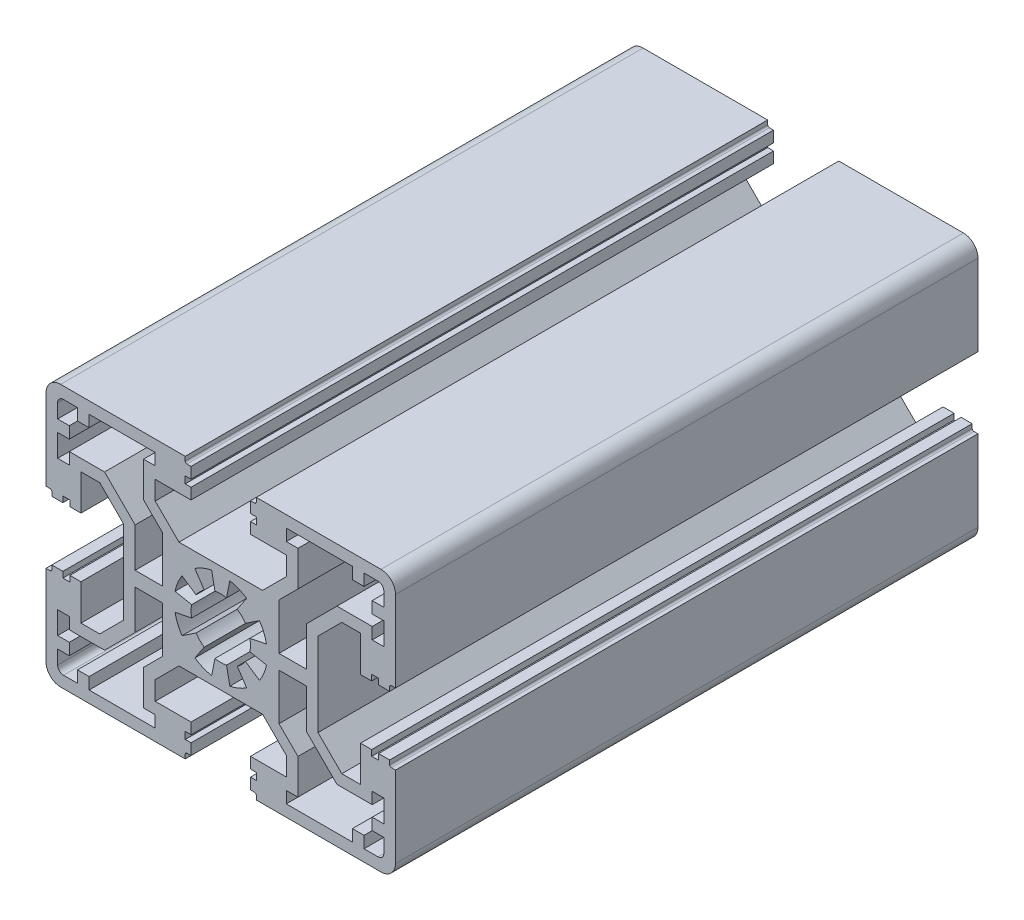
SolidWorks part; units mm, degrees
ref_plane "前视基准面" through (0, 0, 0) normal (0, 0, 1) x (1, 0, 0)
ref_plane "上视基准面" through (0, 0, 0) normal (0, 1, 0) x (1, 0, 0)
ref_plane "右视基准面" through (0, 0, 0) normal (1, 0, 0) x (0, 0, -1)
sketch "草图1" plane through (0, 0, 0) normal (0, 0, 1) x (1, 0, 0)
  line L0 (-5.9772, 23.257) -> (-27.3772, 23.257)
  line L1 (-29.8772, 20.757) -> (-29.8772, 6.857)
  line L2 (7.2944, 9.957) -> (-7.0488, 9.957)
  line L3 (-14.5772, 8.757) -> (-14.5772, 2.007)
  line L4 (6.7746, 5.2016) -> (4.3633, 3.5904)
  line L5 (1.6835, -7.0893) -> (1.1178, -4.245)
  line L6 (-4.3218, -5.8947) -> (-2.7106, -3.4835)
  line L7 (-1.4379, -7.0893) -> (-0.8722, -4.245)
  line L8 (4.5674, -5.8947) -> (2.9562, -3.4835)
  line L9 (6.7746, -3.6875) -> (4.3633, -2.0764)
  line L10 (7.9691, -0.8037) -> (5.1248, -0.2379)
  line L11 (7.9691, 2.3177) -> (5.1248, 1.752)
  line L12 (4.5674, 7.4088) -> (2.9562, 4.9975)
  line L13 (-7.7235, 2.3177) -> (-4.8792, 1.752)
  line L14 (1.6835, 8.6033) -> (1.1178, 5.759)
  line L15 (-1.4379, 8.6033) -> (-0.8722, 5.759)
  line L16 (-4.3218, 7.4088) -> (-2.7106, 4.9975)
  line L17 (-6.529, 5.2016) -> (-4.1177, 3.5904)
  line L18 (-7.7235, -0.8037) -> (-4.8792, -0.2379)
  line L19 (-13.1272, 13.207) -> (-13.1272, 19.257)
  line L20 (-14.1272, 21.257) -> (-22.4778, 21.257)
  line L21 (-24.4778, 21.257) -> (-26.8772, 21.257)
  line L22 (-27.8772, 20.257) -> (-27.8772, 17.8576)
  line L23 (-27.8772, 15.8576) -> (-27.8772, 15.007)
  line L24 (-25.8772, 14.007) -> (-19.8272, 14.007)
  line L25 (-6.529, -3.6875) -> (-4.1177, -2.0764)
  line L26 (-9.8772, 9.957) -> (-9.8772, 2.007)
  line L27 (-14.5772, 2.007) -> (-9.8772, 2.007)
  line L28 (-9.8772, 9.957) -> (-13.1272, 13.207)
  line L29 (-7.0488, 9.957) -> (-11.1272, 14.0354)
  line L30 (-16.5772, 7.9286) -> (-20.6556, 12.007)
  line L31 (-14.5772, 8.757) -> (-19.8272, 14.007)
  line L32 (6.2228, 23.257) -> (27.6228, 23.257)
  line L33 (30.1228, 20.757) -> (30.1228, 6.857)
  line L34 (16.8228, 7.9286) -> (20.9012, 12.007)
  line L35 (7.2944, 9.957) -> (11.3728, 14.0354)
  line L36 (-16.5772, 7.9286) -> (-16.5772, 0.757)
  line L37 (16.8228, 7.9286) -> (16.8228, 0.757)
  line L38 (-5.9772, -21.743) -> (-27.3772, -21.743)
  line L39 (-29.8772, -19.243) -> (-29.8772, -5.343)
  line L40 (7.2944, -8.443) -> (-7.0488, -8.443)
  line L41 (-7.0488, -8.443) -> (-11.1272, -12.5214)
  line L42 (-16.5772, -6.4146) -> (-20.6556, -10.493)
  line L43 (6.2228, -21.743) -> (27.6228, -21.743)
  line L44 (30.1228, -19.243) -> (30.1228, -5.343)
  line L45 (16.8228, -6.4146) -> (20.9012, -10.493)
  line L46 (7.2944, -8.443) -> (11.3728, -12.5214)
  line L47 (-16.5772, -6.4146) -> (-16.5772, 0.757)
  line L48 (16.8228, -6.4146) -> (16.8228, 0.757)
  line L49 (-29.8772, 6.857) -> (-29.1772, 6.857)
  line L50 (-28.8772, 6.557) -> (-28.8772, 5.857)
  line L51 (-28.8772, 5.857) -> (-26.9772, 5.857)
  line L52 (-25.7772, 5.857) -> (-23.8772, 5.857)
  line L53 (-26.9772, 6.857) -> (-25.7772, 6.857)
  line L54 (-25.7772, 5.857) -> (-25.7772, 6.857)
  line L55 (-26.9772, 5.857) -> (-26.9772, 6.857)
  line L56 (-29.8772, -5.343) -> (-29.1772, -5.343)
  line L57 (-28.8772, -5.043) -> (-28.8772, -4.343)
  line L58 (-28.8772, -4.343) -> (-26.9772, -4.343)
  line L59 (-25.7772, -4.343) -> (-23.8772, -4.343)
  line L60 (-26.9772, -5.343) -> (-25.7772, -5.343)
  line L61 (-25.7772, -4.343) -> (-25.7772, -5.343)
  line L62 (-26.9772, -4.343) -> (-26.9772, -5.343)
  line L63 (-23.8772, 12.007) -> (-23.8772, 5.857)
  line L64 (-23.8772, -10.493) -> (-23.8772, -4.343)
  line L65 (-20.6556, 12.007) -> (-23.8772, 12.007)
  line L66 (-20.6556, -10.493) -> (-23.8772, -10.493)
  line L71 (30.1228, 6.857) -> (29.4228, 6.857)
  line L72 (29.1228, 6.557) -> (29.1228, 5.857)
  line L73 (29.1228, 5.857) -> (27.2228, 5.857)
  line L74 (26.0228, 5.857) -> (24.1228, 5.857)
  line L75 (27.2228, 6.857) -> (26.0228, 6.857)
  line L76 (26.0228, 5.857) -> (26.0228, 6.857)
  line L77 (27.2228, 5.857) -> (27.2228, 6.857)
  line L78 (30.1228, -5.343) -> (29.4228, -5.343)
  line L79 (29.1228, -5.043) -> (29.1228, -4.343)
  line L80 (29.1228, -4.343) -> (27.2228, -4.343)
  line L81 (26.0228, -4.343) -> (24.1228, -4.343)
  line L82 (27.2228, -5.343) -> (26.0228, -5.343)
  line L83 (26.0228, -4.343) -> (26.0228, -5.343)
  line L84 (27.2228, -4.343) -> (27.2228, -5.343)
  line L85 (24.1228, 12.007) -> (24.1228, 5.857)
  line L86 (24.1228, -10.493) -> (24.1228, -4.343)
  line L87 (20.9012, 12.007) -> (24.1228, 12.007)
  line L88 (20.9012, -10.493) -> (24.1228, -10.493)
  line L89 (-5.9772, 23.257) -> (-5.9772, 22.557)
  line L90 (-5.6772, 22.257) -> (-4.9772, 22.257)
  line L91 (-4.9772, 22.257) -> (-4.9772, 20.357)
  line L92 (-4.9772, 19.157) -> (-4.9772, 17.257)
  line L93 (-5.9772, 20.357) -> (-5.9772, 19.157)
  line L94 (-4.9772, 19.157) -> (-5.9772, 19.157)
  line L95 (-4.9772, 20.357) -> (-5.9772, 20.357)
  line L96 (6.2228, 23.257) -> (6.2228, 22.557)
  line L97 (5.9228, 22.257) -> (5.2228, 22.257)
  line L98 (5.2228, 22.257) -> (5.2228, 20.357)
  line L99 (5.2228, 19.157) -> (5.2228, 17.257)
  line L100 (6.2228, 20.357) -> (6.2228, 19.157)
  line L101 (5.2228, 19.157) -> (6.2228, 19.157)
  line L102 (5.2228, 20.357) -> (6.2228, 20.357)
  line L103 (-11.1272, 17.257) -> (-4.9772, 17.257)
  line L104 (11.3728, 17.257) -> (5.2228, 17.257)
  line L105 (-11.1272, 14.0354) -> (-11.1272, 17.257)
  line L106 (11.3728, 14.0354) -> (11.3728, 17.257)
  line L107 (-5.9772, -21.743) -> (-5.9772, -21.043)
  line L108 (-5.6772, -20.743) -> (-4.9772, -20.743)
  line L109 (-4.9772, -20.743) -> (-4.9772, -18.843)
  line L110 (-4.9772, -17.643) -> (-4.9772, -15.743)
  line L111 (-5.9772, -18.843) -> (-5.9772, -17.643)
  line L112 (-4.9772, -17.643) -> (-5.9772, -17.643)
  line L113 (-4.9772, -18.843) -> (-5.9772, -18.843)
  line L114 (6.2228, -21.743) -> (6.2228, -21.043)
  line L115 (5.9228, -20.743) -> (5.2228, -20.743)
  line L116 (5.2228, -20.743) -> (5.2228, -18.843)
  line L117 (5.2228, -17.643) -> (5.2228, -15.743)
  line L118 (6.2228, -18.843) -> (6.2228, -17.643)
  line L119 (5.2228, -17.643) -> (6.2228, -17.643)
  line L120 (5.2228, -18.843) -> (6.2228, -18.843)
  line L121 (-11.1272, -15.743) -> (-4.9772, -15.743)
  line L122 (11.3728, -15.743) -> (5.2228, -15.743)
  line L123 (-11.1272, -12.5214) -> (-11.1272, -15.743)
  line L124 (11.3728, -12.5214) -> (11.3728, -15.743)
  line L125 (-27.8772, 15.007) -> (-27.8772, 14.007)
  line L126 (-27.8772, 14.007) -> (-27.8772, 12.007)
  line L127 (-27.8772, 12.007) -> (-25.8772, 12.007)
  line L128 (-25.8772, 12.007) -> (-25.8772, 14.007)
  line L129 (-27.8772, 17.8576) -> (-25.8772, 17.8576)
  line L130 (-27.8772, 15.8576) -> (-25.8772, 15.8576)
  line L131 (-25.8772, 17.8576) -> (-25.8772, 15.8576)
  line L132 (-24.4778, 21.257) -> (-24.4778, 19.257)
  line L133 (-22.4778, 21.257) -> (-22.4778, 19.257)
  line L134 (-24.4778, 19.257) -> (-22.4778, 19.257)
  line L135 (-14.1272, 21.257) -> (-13.1272, 21.257)
  line L136 (-13.1272, 21.257) -> (-11.1272, 21.257)
  line L137 (-11.1272, 21.257) -> (-11.1272, 19.257)
  line L138 (-11.1272, 19.257) -> (-13.1272, 19.257)
  line L139 (13.3728, 19.257) -> (11.3728, 19.257)
  line L140 (11.3728, 19.257) -> (11.3728, 21.257)
  line L141 (11.3728, 21.257) -> (13.3728, 21.257)
  line L142 (13.3728, 21.257) -> (14.3728, 21.257)
  line L143 (14.3728, 21.257) -> (22.7234, 21.257)
  line L144 (22.7234, 21.257) -> (22.7234, 19.257)
  line L145 (22.7234, 19.257) -> (24.7234, 19.257)
  line L146 (24.7234, 19.257) -> (24.7234, 21.257)
  line L147 (24.7234, 21.257) -> (27.1228, 21.257)
  line L148 (28.1228, 20.257) -> (28.1228, 17.8576)
  line L149 (28.1228, 17.8576) -> (26.1228, 17.8576)
  line L150 (26.1228, 17.8576) -> (26.1228, 15.8576)
  line L151 (26.1228, 15.8576) -> (28.1228, 15.8576)
  line L152 (28.1228, 15.8576) -> (28.1228, 15.007)
  line L153 (28.1228, 15.007) -> (28.1228, 14.007)
  line L154 (28.1228, 14.007) -> (28.1228, 12.007)
  line L155 (28.1228, 12.007) -> (26.1228, 12.007)
  line L156 (26.1228, 12.007) -> (26.1228, 14.007)
  line L157 (26.1228, 14.007) -> (20.0728, 14.007)
  line L158 (20.0728, 14.007) -> (14.8228, 8.757)
  line L159 (14.8228, 8.757) -> (14.8228, 2.007)
  line L160 (14.8228, 2.007) -> (10.1228, 2.007)
  line L161 (10.1228, 2.007) -> (10.1228, 9.957)
  line L162 (10.1228, 9.957) -> (13.3728, 13.207)
  line L163 (13.3728, 13.207) -> (13.3728, 19.257)
  line L164 (-13.1272, -17.743) -> (-11.1272, -17.743)
  line L165 (-11.1272, -17.743) -> (-11.1272, -19.743)
  line L166 (-11.1272, -19.743) -> (-13.1272, -19.743)
  line L167 (-13.1272, -19.743) -> (-14.1272, -19.743)
  line L168 (-14.1272, -19.743) -> (-22.4778, -19.743)
  line L169 (-22.4778, -19.743) -> (-22.4778, -17.743)
  line L170 (-22.4778, -17.743) -> (-24.4778, -17.743)
  line L171 (-24.4778, -17.743) -> (-24.4778, -19.743)
  line L172 (-24.4778, -19.743) -> (-26.8772, -19.743)
  line L173 (-27.8772, -18.743) -> (-27.8772, -16.3436)
  line L174 (-27.8772, -16.3436) -> (-25.8772, -16.3436)
  line L175 (-25.8772, -16.3436) -> (-25.8772, -14.3436)
  line L176 (-25.8772, -14.3436) -> (-27.8772, -14.3436)
  line L177 (-27.8772, -14.3436) -> (-27.8772, -13.493)
  line L178 (-27.8772, -13.493) -> (-27.8772, -12.493)
  line L179 (-27.8772, -12.493) -> (-27.8772, -10.493)
  line L180 (-27.8772, -10.493) -> (-25.8772, -10.493)
  line L181 (-25.8772, -10.493) -> (-25.8772, -12.493)
  line L182 (-25.8772, -12.493) -> (-19.8272, -12.493)
  line L183 (-19.8272, -12.493) -> (-14.5772, -7.243)
  line L184 (-14.5772, -7.243) -> (-14.5772, -0.493)
  line L185 (-14.5772, -0.493) -> (-9.8772, -0.493)
  line L186 (-9.8772, -0.493) -> (-9.8772, -8.443)
  line L187 (-9.8772, -8.443) -> (-13.1272, -11.693)
  line L188 (-13.1272, -11.693) -> (-13.1272, -17.743)
  line L189 (13.3728, -17.743) -> (11.3728, -17.743)
  line L190 (11.3728, -17.743) -> (11.3728, -19.743)
  line L191 (11.3728, -19.743) -> (13.3728, -19.743)
  line L192 (13.3728, -19.743) -> (14.3728, -19.743)
  line L193 (14.3728, -19.743) -> (22.7234, -19.743)
  line L194 (22.7234, -19.743) -> (22.7234, -17.743)
  line L195 (22.7234, -17.743) -> (24.7234, -17.743)
  line L196 (24.7234, -17.743) -> (24.7234, -19.743)
  line L197 (24.7234, -19.743) -> (27.1228, -19.743)
  line L198 (28.1228, -18.743) -> (28.1228, -16.3436)
  line L199 (28.1228, -16.3436) -> (26.1228, -16.3436)
  line L200 (26.1228, -16.3436) -> (26.1228, -14.3436)
  line L201 (26.1228, -14.3436) -> (28.1228, -14.3436)
  line L202 (28.1228, -14.3436) -> (28.1228, -13.493)
  line L203 (28.1228, -13.493) -> (28.1228, -12.493)
  line L204 (28.1228, -12.493) -> (28.1228, -10.493)
  line L205 (28.1228, -10.493) -> (26.1228, -10.493)
  line L206 (26.1228, -10.493) -> (26.1228, -12.493)
  line L207 (26.1228, -12.493) -> (20.0728, -12.493)
  line L208 (20.0728, -12.493) -> (14.8228, -7.243)
  line L209 (14.8228, -7.243) -> (14.8228, -0.493)
  line L210 (14.8228, -0.493) -> (10.1228, -0.493)
  line L211 (10.1228, -0.493) -> (10.1228, -8.443)
  line L212 (10.1228, -8.443) -> (13.3728, -11.693)
  line L213 (13.3728, -11.693) -> (13.3728, -17.743)
  arc A0 (-27.3772, 23.257) -> (-29.8772, 20.757) centre (-27.3772, 20.757) ccw
  arc A1 (-1.4379, 8.6033) -> (-4.3218, 7.4088) centre (0.1228, 0.757) ccw
  arc A2 (-6.529, 5.2016) -> (-7.7235, 2.3177) centre (0.1228, 0.757) ccw
  arc A3 (-0.8722, -4.245) -> (1.1178, -4.245) centre (0.1228, 0.757) ccw
  arc A4 (2.9562, -3.4835) -> (4.3633, -2.0764) centre (0.1228, 0.757) ccw
  arc A5 (5.1248, -0.2379) -> (5.1248, 1.752) centre (0.1228, 0.757) ccw
  arc A6 (4.3633, 3.5904) -> (2.9562, 4.9975) centre (0.1228, 0.757) ccw
  arc A7 (1.1178, 5.759) -> (-0.8722, 5.759) centre (0.1228, 0.757) ccw
  arc A8 (-2.7106, 4.9975) -> (-4.1177, 3.5904) centre (0.1228, 0.757) ccw
  arc A9 (-4.8792, 1.752) -> (-4.8792, -0.2379) centre (0.1228, 0.757) ccw
  arc A10 (-4.1177, -2.0764) -> (-2.7106, -3.4835) centre (0.1228, 0.757) ccw
  arc A11 (-4.3218, -5.8947) -> (-1.4379, -7.0893) centre (0.1228, 0.757) ccw
  arc A12 (1.6835, -7.0893) -> (4.5674, -5.8947) centre (0.1228, 0.757) ccw
  arc A13 (6.7746, -3.6875) -> (7.9691, -0.8037) centre (0.1228, 0.757) ccw
  arc A14 (7.9691, 2.3177) -> (6.7746, 5.2016) centre (0.1228, 0.757) ccw
  arc A15 (4.5674, 7.4088) -> (1.6835, 8.6033) centre (0.1228, 0.757) ccw
  arc A16 (-7.7235, -0.8037) -> (-6.529, -3.6875) centre (0.1228, 0.757) ccw
  arc A17 (-26.8772, 21.257) -> (-27.8772, 20.257) centre (-26.8772, 20.257) ccw
  arc A18 (30.1228, 20.757) -> (27.6228, 23.257) centre (27.6228, 20.757) ccw
  arc A19 (-29.8772, -19.243) -> (-27.3772, -21.743) centre (-27.3772, -19.243) ccw
  arc A20 (27.6228, -21.743) -> (30.1228, -19.243) centre (27.6228, -19.243) ccw
  arc A21 (-28.8772, 6.557) -> (-29.1772, 6.857) centre (-29.1772, 6.557) ccw
  arc A22 (-29.1772, -5.343) -> (-28.8772, -5.043) centre (-29.1772, -5.043) ccw
  arc A23 (29.4228, 6.857) -> (29.1228, 6.557) centre (29.4228, 6.557) ccw
  arc A24 (29.1228, -5.043) -> (29.4228, -5.343) centre (29.4228, -5.043) ccw
  arc A25 (-5.9772, 22.557) -> (-5.6772, 22.257) centre (-5.6772, 22.557) ccw
  arc A26 (5.9228, 22.257) -> (6.2228, 22.557) centre (5.9228, 22.557) ccw
  arc A27 (-5.6772, -20.743) -> (-5.9772, -21.043) centre (-5.6772, -21.043) ccw
  arc A28 (6.2228, -21.043) -> (5.9228, -20.743) centre (5.9228, -21.043) ccw
  arc A29 (28.1228, 20.257) -> (27.1228, 21.257) centre (27.1228, 20.257) ccw
  arc A30 (-27.8772, -18.743) -> (-26.8772, -19.743) centre (-26.8772, -18.743) ccw
  arc A31 (27.1228, -19.743) -> (28.1228, -18.743) centre (27.1228, -18.743) ccw
extrude "凸台-拉伸1" add sketch "草图1" along normal blind 100
